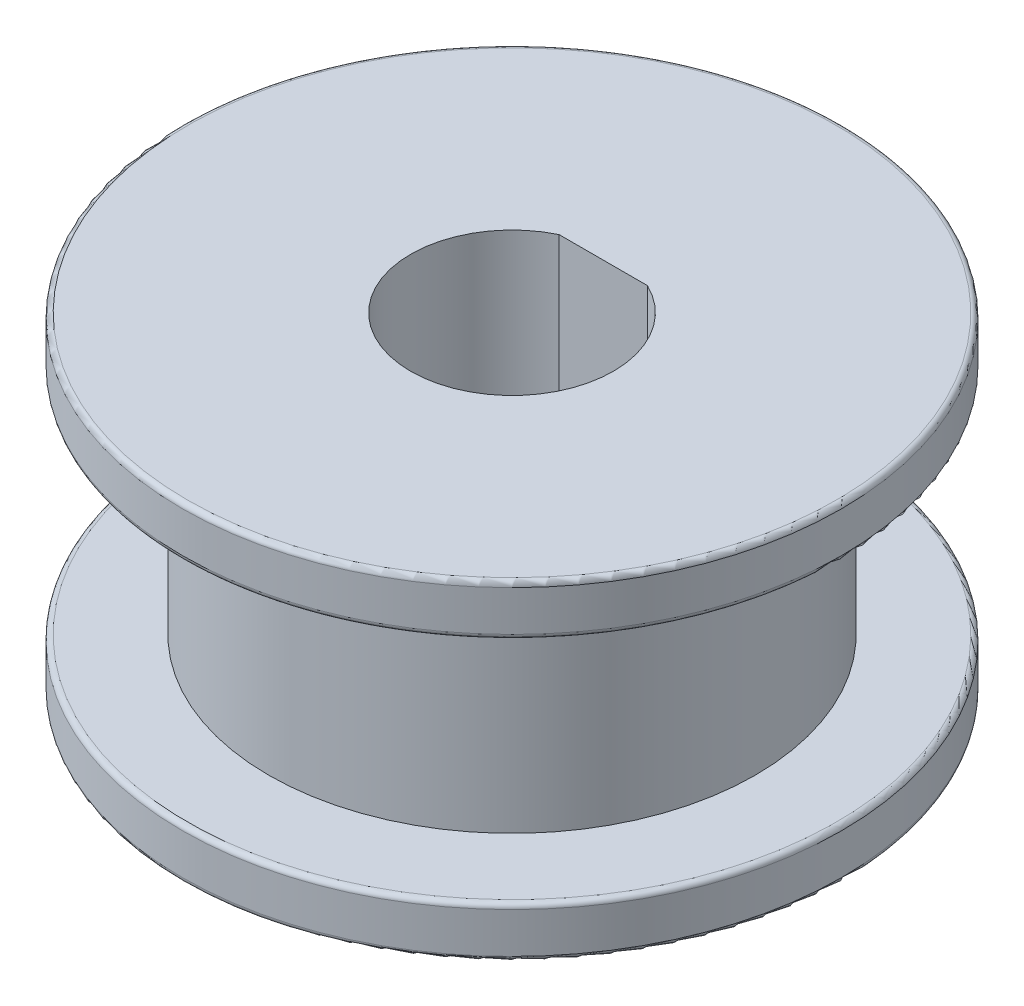
SolidWorks part; units mm, degrees
ref_plane "前视基准面" through (0, 0, 0) normal (0, 0, 1) x (1, 0, 0)
ref_plane "上视基准面" through (0, 0, 0) normal (0, 1, 0) x (1, 0, 0)
ref_plane "右视基准面" through (0, 0, 0) normal (1, 0, 0) x (0, 0, -1)
sketch "草图2" plane through (0, 0, 0) normal (0, 1, 0) x (1, 0, 0)
  line L1 (0.8718, 1.8) -> (-0.8718, 1.8)
  circle A0 centre (0, 0) radius 6.5
  arc A1 (-0.8718, 1.8) -> (0.8718, 1.8) centre (0, 0) ccw
extrude "凸台-拉伸1" add sketch "草图2" along normal blind 6.5
ref_plane "基准面1" through (0, 1, 0) normal (0, -1, 0) x (-1, 0, 0)
sketch "草图4" plane through (0, 1, 0) normal (0, -1, 0) x (-1, 0, 0)
  circle A0 centre (0, 0) radius 6.5
  circle A1 centre (0, 0) radius 4.8
extrude "切除-拉伸1" cut sketch "草图4" against normal blind 4.5
fillet "圆角1" radius 0.1 4 edges at (0, 0, 6.5) (0, 6.5, 6.5) (0, 1, -6.5) (0, 5.5, -6.5)
